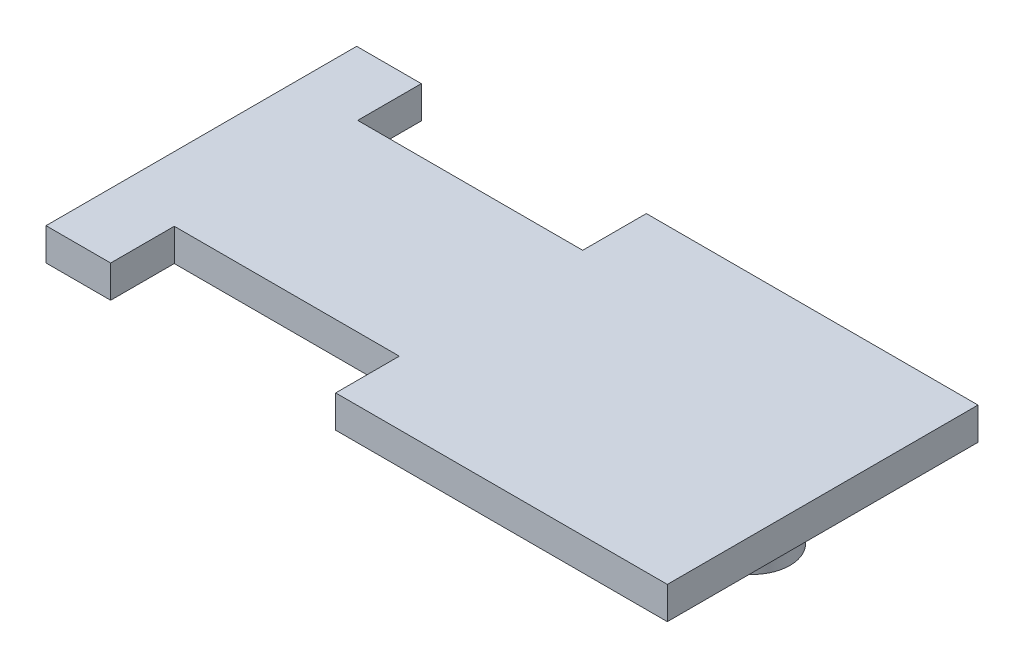
SolidWorks part; units mm, degrees
ref_plane "Front Plane" through (0, 0, 0) normal (0, 0, 1) x (1, 0, 0)
ref_plane "Top Plane" through (0, 0, 0) normal (0, 1, 0) x (1, 0, 0)
ref_plane "Right Plane" through (0, 0, 0) normal (1, 0, 0) x (0, 0, -1)
sketch "Sketch1" plane through (0, 0, 0) normal (0, 1, 0) x (1, 0, 0)
  line L1 (-103.7167, 55.6948) -> (-2.1167, 55.6948)
  line L2 (-103.7167, 55.6948) -> (-103.7167, 4.8948)
  line L3 (-103.7167, 4.8948) -> (-2.1167, 4.8948)
  line L4 (-2.1167, 55.6948) -> (-2.1167, 4.8948)
  line L5 (-103.7167, 55.6948) -> (-2.1167, 4.8948) construction
  line L6 (-103.7167, 4.8948) -> (-2.1167, 55.6948) construction
  point P0 (-52.9167, 30.2948)
  dimension "D1" = 50.8
  dimension "D2" = 101.6
extrude "Boss-Extrude1" add sketch "Sketch1" along normal blind 10
sketch "Sketch3" plane through (0, 10, 0) normal (0, 1, 0) x (1, 0, 0)
  line L1 (-93.1444, 15.3005) -> (-56.3485, 15.3005)
  line L2 (-93.1444, 15.3005) -> (-93.1444, 2.7466)
  line L3 (-93.1444, 2.7466) -> (-56.3485, 2.7466)
  line L4 (-56.3485, 15.3005) -> (-56.3485, 2.7466)
  line L5 (-93.1444, 15.3005) -> (-56.3485, 2.7466) construction
  line L6 (-93.1444, 2.7466) -> (-56.3485, 15.3005) construction
  line L15 (-93.1444, 60.383) -> (-56.3485, 60.383)
  line L16 (-56.3485, 45.289) -> (-56.3485, 60.383)
  line L17 (-93.1444, 45.289) -> (-56.3485, 45.289)
  line L18 (-93.1444, 45.289) -> (-93.1444, 60.383)
  point P0 (-74.7464, 9.0236)
  point P9 (0, 0)
  line M14 (-103.7167, 4.8948) -> (-2.1167, 4.8948)
extrude "Cut-Extrude4" cut sketch "Sketch3" against normal blind 10 contours L4 L1 L2 M14 | L15 L16 L17 L18
sketch "Sketch5" plane through (0, 0, 0) normal (0, -1, 0) x (1, 0, 0)
  line L0 (-2.1167, -30.2948) -> (-103.7167, -30.2948)
  line L1 (-2.1167, -4.8948) -> (-2.1167, -55.6948) construction
  line L2 (-103.7167, -55.6948) -> (-103.7167, -4.8948) construction
  circle A0 centre (-13.6316, -30.2948) radius 6.1699
extrude "Boss-Extrude3" add sketch "Sketch5" along normal blind 7.4125 contours L0 A0 | L0 A0
sketch "Sketch7" plane through (0, -7.4125, 0) normal (0, -1, 0) x (1, 0, 0)
  line L0 (-15.3631, -27.5351) -> (-11.4671, -33.3792)
  arc A0 (-11.4671, -33.3792) -> (-15.3631, -27.5351) centre (-13.4151, -30.4571) ccw
revolve "Revolve3" add sketch "Sketch7" angle 360 about L0
sketch "Sketch8" plane through (0, 10, 0) normal (0, 1, 0) x (1, 0, 0)
  line L1 (5.3319, 58.691) -> (-106.6536, 58.691)
  line L2 (5.3319, 58.691) -> (5.3319, 1.7776)
  line L3 (5.3319, 1.7776) -> (-106.6536, 1.7776)
  line L4 (-106.6536, 58.691) -> (-106.6536, 1.7776)
extrude "Cut-Extrude5" cut sketch "Sketch8" against normal blind 4.716
